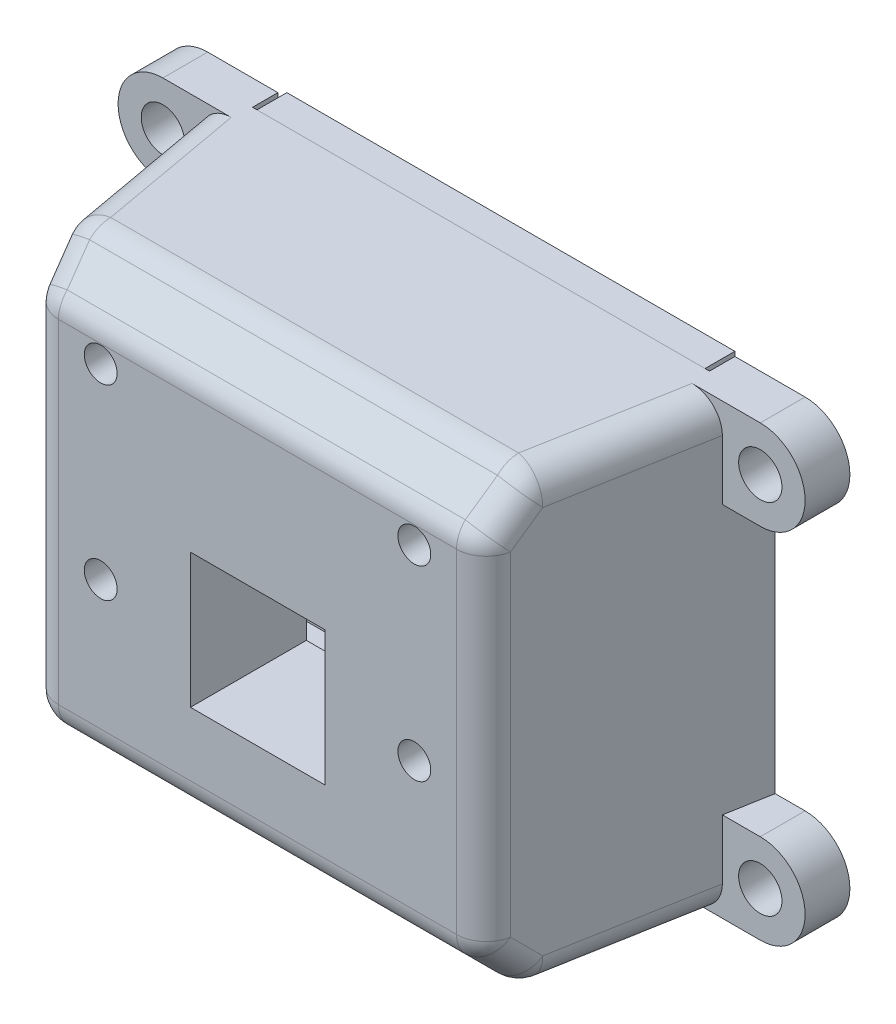
SolidWorks part; units mm, degrees
ref_plane "Front Plane" through (0, 0, 0) normal (0, 0, 1) x (1, 0, 0)
ref_plane "Top Plane" through (0, 0, 0) normal (0, 1, 0) x (1, 0, 0)
ref_plane "Right Plane" through (0, 0, 0) normal (1, 0, 0) x (0, 0, -1)
sketch "Sketch1" plane through (0, 0, 6.763) normal (0, 0, 1) x (1, 0, 0)
  line L1 (-15, -15) -> (15, -15)
  line L2 (-15, -15) -> (-15, 15)
  line L3 (-15, 15) -> (15, 15)
  line L4 (15, -15) -> (15, 15)
  line L5 (-15, -15) -> (15, 15) construction
  line L6 (-15, 15) -> (15, -15) construction
  point P0 (0, 0)
  dimension "D1" = 30
extrude "Boss-Extrude1" add sketch "Sketch1" along normal blind 2
sketch "Sketch2" plane through (0, 0, 6.763) normal (0, 0, -1) x (-1, 0, 0)
  line L0 (13, -15) -> (13, 13)
  line L1 (13, 13) -> (-13, 13)
  line L2 (-13, 13) -> (-13, -15)
  line L3 (-15, -15) -> (-13, -15)
  line L4 (-15, 15) -> (-15, -15)
  line L5 (-15, -15) -> (15, -15)
  line L6 (15, -15) -> (15, 15)
  line L7 (15, 15) -> (-15, 15)
  line L8 (-15, 15) -> (-15, -15)
  line L10 (15, -15) -> (15, 15)
  line L11 (15, 15) -> (-15, 15)
  line L12 (13, -15) -> (15, -15)
  dimension "D1" = 0
  dimension "D2" = 2
extrude "Boss-Extrude2" add sketch "Sketch2" along normal offset from surface (12.963 mm away) 3
sketch "Sketch3" plane through (0, 0, 6.763) normal (0, 0, -1) x (-1, 0, 0)
  line L0 (-10.5, 0.4953) -> (-13, 0.4953)
  line L1 (-13, 13) -> (-13, -15) construction
  line L2 (-13, 0.4953) -> (-13, -5.5047)
  line L3 (-13, -5.5047) -> (-10.5, -5.5047)
  line L4 (-13, 12.9953) -> (-10.5, 12.9953)
  line L5 (-13, -15) -> (-13, 13) construction
  line L6 (-10.5, 6.9953) -> (-13, 6.9953)
  line L7 (-13, 6.9953) -> (-13, 12.9953)
  line L8 (13, 12.9953) -> (10.5, 12.9953)
  line L9 (13, 13) -> (13, -15) construction
  line L10 (10.5, 6.9953) -> (13, 6.9953)
  line L12 (13, 6.9953) -> (13, 12.9953)
  line L13 (13, 0.4953) -> (10.5, 0.4953)
  line L14 (10.5, -5.5047) -> (13, -5.5047)
  line L15 (13, -5.5047) -> (13, 0.4953)
  circle A5 centre (-10.5, 9.9953) radius 1.1 construction
  arc A8 (-10.5, -5.5047) -> (-10.5, 0.4953) centre (-10.5, -2.5047) ccw
  arc A9 (-10.5, 12.9953) -> (-10.5, 6.9953) centre (-10.5, 9.9953) cw
  arc A11 (10.5, 12.9953) -> (10.5, 6.9953) centre (10.5, 9.9953) ccw
  arc A13 (10.5, 0.4953) -> (10.5, -5.5047) centre (10.5, -2.5047) ccw
  arc A15 (-12.5, -3.4212) -> (-12.5, -1.5882) centre (-10.5, -2.5047) ccw construction
  arc A16 (12.5, 9.9953) -> (10.5, 11.9953) centre (10.5, 9.9953) ccw construction
  arc A17 (12.5, -1.5882) -> (12.5, -3.4212) centre (10.5, -2.5047) ccw construction
  dimension "D1" = 6
extrude "Boss-Extrude3" add sketch "Sketch3" along normal up to surface (5.763 mm away)
sketch "Sketch4" plane through (0, 0, 6.763) normal (0, 0, -1) x (-1, 0, 0)
  line L1 (13, -12.3667) -> (-13, -12.3667)
  line L2 (13, -12.3667) -> (13, -15)
  line L3 (13, -15) -> (-13, -15)
  line L4 (-13, -12.3667) -> (-13, -15)
  line L5 (-11.0493, -11.8667) -> (11.1507, -11.8667) construction
  line L6 (-11.0493, -11.8667) -> (11.1507, -11.8667) construction
  line L7 (13, 6.9953) -> (13, 0.4953) construction
  dimension "D1" = 0.5
extrude "Boss-Extrude4" add sketch "Sketch4" along normal up to surface (6.763 mm away) up to plane "Front Plane"
sketch "Sketch6" plane through (0, 0, -6.2) normal (0, 0, -1) x (-1, 0, 0)
  line L1 (-15, 15) -> (15, 15)
  line L2 (-15, 15) -> (-15, -15)
  line L3 (-15, -15) -> (15, -15)
  line L4 (15, 15) -> (15, -15)
extrude "Boss-Extrude5" add sketch "Sketch6" along normal blind 2 separate body
sketch "Sketch8" plane through (0, 0, 8.763) normal (0, 0, 1) x (1, 0, 0)
  line L0 (-3.9917, 1.5922) -> (-3.9917, -6.4078) construction
  line L1 (-3.9917, -6.4078) -> (4.0083, -6.4078) construction
  line L2 (4.0083, -6.4078) -> (4.0083, 1.5922) construction
  line L3 (4.0083, 1.5922) -> (-3.9917, 1.5922) construction
  line L4 (-3.9917, 1.5922) -> (-3.9917, -6.4078) construction
  line L5 (-3.9917, -6.4078) -> (4.0083, -6.4078) construction
  line L6 (4.0083, -6.4078) -> (4.0083, 1.5922) construction
  line L7 (4.0083, 1.5922) -> (-3.9917, 1.5922) construction
  line L8 (-4.4917, 2.0922) -> (-4.4917, -6.9078)
  line L9 (-4.4917, -6.9078) -> (4.5083, -6.9078)
  line L10 (4.5083, -6.9078) -> (4.5083, 2.0922)
  line L11 (4.5083, 2.0922) -> (-4.4917, 2.0922)
  dimension "D1" = 0.5
extrude "Cut-Extrude1" cut sketch "Sketch8" against normal through all
sketch "Sketch9" plane through (0, 0, 6.763) normal (0, 0, -1) x (-1, 0, 0)
  line L0 (5.4917, -7.9078) -> (5.4917, 3.0922)
  line L1 (5.4917, 3.0922) -> (-5.5083, 3.0922)
  line L2 (-5.5083, 3.0922) -> (-5.5083, -7.9078)
  line L3 (-5.5083, -7.9078) -> (5.4917, -7.9078)
  line L4 (4.4917, -6.9078) -> (4.4917, 2.0922)
  line L5 (-4.5083, -6.9078) -> (4.4917, -6.9078)
  line L6 (-4.5083, 2.0922) -> (-4.5083, -6.9078)
  line L7 (4.4917, 2.0922) -> (-4.5083, 2.0922)
  line L8 (4.4917, -6.9078) -> (4.4917, 2.0922)
  line L9 (-4.5083, -6.9078) -> (4.4917, -6.9078)
  line L10 (-4.5083, 2.0922) -> (-4.5083, -6.9078)
  line L11 (4.4917, 2.0922) -> (-4.5083, 2.0922)
  dimension "D1" = 0
  dimension "D2" = 1
extrude "Boss-Extrude7" add sketch "Sketch9" along normal up to surface (5.763 mm away)
sketch "Sketch10" plane through (0, 0, 1) normal (0, 0, -1) x (-1, 0, 0)
  line L0 (5.4917, 3.0922) -> (-5.5083, 3.0922) construction
  line L1 (4.4917, 2.0922) -> (-4.5083, 2.0922)
  line L2 (4.4917, 2.0922) -> (4.4917, 3.0922)
  line L3 (4.4917, 3.0922) -> (-4.5083, 3.0922)
  line L4 (-4.5083, 2.0922) -> (-4.5083, 3.0922)
extrude "Cut-Extrude2" cut sketch "Sketch10" against normal offset from surface (2.1 mm away) 1
sketch "Sketch11" plane through (0, 0, 6.763) normal (0, 0, -1) x (-1, 0, 0)
  line L0 (13, -15) -> (13, 13) construction
  line L1 (-13, 13) -> (13, 13)
  line L2 (-13, 13) -> (-13, 12.999)
  line L3 (-13, 12.999) -> (13, 12.999)
  line L4 (13, 13) -> (13, 12.999)
  dimension "D1" = 0.001
extrude "Boss-Extrude8" add sketch "Sketch11" along normal up to surface (12.963 mm away)
sketch "Sketch13" plane through (0, -15, 0) normal (0, -1, 0) x (1, 0, 0)
  line L0 (13, -6.2) -> (15, -6.2) construction
  line L1 (13.75, -6.2) -> (13, -6.2)
  line L2 (13.75, -6.2) -> (13.75, 0)
  line L3 (13.75, 0) -> (13, 0)
  line L4 (13, -6.2) -> (13, 0)
  line L5 (13, -6.2) -> (13, 0) construction
  line L6 (-13, 0) -> (13, 0) construction
  line L7 (15, 8.763) -> (15, -6.2) construction
  line L8 (0, 5.5223) -> (0, 0) construction
  line L14 (-13, -6.2) -> (-13, 0)
  line L15 (-13.75, 0) -> (-13, 0)
  line L16 (-13.75, -6.2) -> (-13.75, 0)
  line L17 (-13.75, -6.2) -> (-13, -6.2)
  dimension "D1" = 1.25
extrude "Cut-Extrude3" cut sketch "Sketch13" against normal up to surface (27.999 mm away) up to face at (0, 12.999, 0.2815)
sketch "Sketch7" plane through (0, -15, 0) normal (0, -1, 0) x (1, 0, 0)
  line L0 (15, -6.2) -> (-15, -6.2) construction
  line L1 (13.5, -6.2) -> (-13.5, -6.2)
  line L2 (13.5, -6.2) -> (13.5, -0.25)
  line L3 (13.5, -0.25) -> (-13.5, -0.25)
  line L4 (-13.5, -6.2) -> (-13.5, -0.25)
  line L5 (13.75, -0.25) -> (13.5, -0.25) construction
  line L7 (13.5, 0) -> (13.5, -0.25) construction
  line L8 (-13.75, 0) -> (13.75, 0) construction
  line L9 (-13.75, -0.25) -> (-13.5, -0.25) construction
  line L10 (-13.75, 0) -> (-13.75, -6.2) construction
  line L11 (13.75, -6.2) -> (13.75, 0) construction
  dimension "D1" = 0.25
extrude "Boss-Extrude6" add sketch "Sketch7" against normal blind 2
sketch "Sketch12" plane through (0, -15, 0) normal (0, -1, 0) x (1, 0, 0)
  line L0 (13.5, -0.25) -> (-13.5, -0.25) construction
  line L1 (-12.5, -0.25) -> (-13.5, -0.25)
  line L2 (-12.5, -0.25) -> (-12.5, -6.2)
  line L3 (-12.5, -6.2) -> (-13.5, -6.2)
  line L4 (-13.5, -0.25) -> (-13.5, -6.2)
  line L6 (12.5, -0.25) -> (13.5, -0.25)
  line L7 (12.5, -0.25) -> (12.5, -6.2)
  line L8 (12.5, -6.2) -> (13.5, -6.2)
  line L9 (13.5, -0.25) -> (13.5, -6.2)
  dimension "D1" = 1
extrude "Boss-Extrude10" add sketch "Sketch12" against normal up to surface (27.999 mm away) up to face at (0, 12.999, 0.1407)
sketch "Sketch17" plane through (0, -15, 0) normal (0, -1, 0) x (1, 0, 0)
  line L0 (15, 8.763) -> (18, -7.9)
  line L1 (18, -7.9) -> (15.3, -7.9)
  line L2 (15.3, -7.9) -> (15.3, -6.2)
  line L3 (15.3, -6.2) -> (15, -6.2)
  line L4 (15, -6.2) -> (15, 8.763)
  line L5 (15, -8.2) -> (15, -6.2) construction
  line L7 (15, 8.763) -> (15, -6.2) construction
  line L8 (0, 0) -> (0, 4.7808) construction
  line L10 (-15.3, -6.2) -> (-15, -6.2)
  line L11 (-15.3, -7.9) -> (-15.3, -6.2)
  line L12 (-18, -7.9) -> (-15.3, -7.9)
  line L13 (-15, 8.763) -> (-18, -7.9)
  line L14 (-15, -6.2) -> (-15, 8.763)
  line L15 (15, -8.2) -> (-15, -8.2) construction
  dimension "D1" = 0.3
  dimension "D2" = 3
  dimension "D3" = 0.3
extrude "Boss-Extrude12" add sketch "Sketch17" against normal up to surface (30 mm away) up to face at (0, 15, 1.2815)
sketch "Sketch18" plane through (0, 0, -7.9) normal (0, 0, -1) x (-1, 0, 0)
  line L1 (-20, -12) -> (20, -12)
  line L2 (-20, -12) -> (-20, 12)
  line L3 (-20, 12) -> (20, 12)
  line L4 (20, -12) -> (20, 12)
  line L5 (-20, -12) -> (20, 12) construction
  line L6 (-20, 12) -> (20, -12) construction
  point P0 (0, 0)
  dimension "D1" = 40
  dimension "D2" = 24
sketch "Sketch19" plane through (0, 0, -7.9) normal (0, 0, -1) x (-1, 0, 0)
  line L0 (-15.3, 15) -> (-20, 15)
  line L1 (-20, -12) -> (-20, 12) construction
  line L2 (-20, 9) -> (-15.3, 9)
  line L4 (-15.3, 9) -> (-15.3, 15)
  line L5 (15.3, 15) -> (20, 15)
  line L6 (20, 9) -> (15.3, 9)
  line L8 (15.3, 9) -> (15.3, 15)
  line L9 (-15.3, -15) -> (-20, -15)
  line L10 (-20, -9) -> (-15.3, -9)
  line L11 (-15.3, -9) -> (-15.3, -15)
  line L12 (15.3, -15) -> (20, -15)
  line L13 (20, -12) -> (20, 12) construction
  line L14 (20, -9) -> (15.3, -9)
  line L15 (15.3, -9) -> (15.3, -15)
  line L16 (-15.3, 15) -> (-15.3, -15) construction
  arc A0 (-20, 15) -> (-20, 9) centre (-20, 12) ccw
  arc A1 (20, 15) -> (20, 9) centre (20, 12) cw
  arc A2 (-20, -15) -> (-20, -9) centre (-20, -12) cw
  arc A3 (20, -15) -> (20, -9) centre (20, -12) ccw
extrude "Boss-Extrude13" add sketch "Sketch19" against normal blind 3
hole_wizard "M2.5 Clearance Hole1" positions "Sketch20" profile "Sketch21" hole size "M2.5" standard "ANSI Metric" end condition through all
sketch "Sketch20" plane through (0, 0, -4.9) normal (0, 0, 1) x (1, 0, 0)
  point P0 (-20, 12)
  point P3 (20, 12)
  point P6 (20, -12)
  point P9 (-20, -12)
sketch "Sketch21" plane through (-20, 12, -4.9) normal (1, 0, 0) x (0, -1, 0)
  line L0 (0, 0) -> (0, 3.3)
  line L1 (0, 3.3) -> (1.45, 3.3)
  line L2 (1.45, 3.3) -> (1.45, 0)
  line L5 (1.45, 0) -> (0, 0)
  line L11 (0, -6.35) -> (0, 107.95) construction
  dimension "Thru Hole Dia." = 2.9
  dimension "Thru Hole Depth" = 3.3
chamfer "Chamfer1" distance 3 angle 45 2 edges at (0, 15, 8.763) (0, -15, 8.763)
sketch "Sketch22" plane through (0, -15, 0) normal (0, -1, 0) x (1, 0, 0)
  line L0 (13.5, -0.25) -> (-13.5, -0.25) construction
  line L1 (-9.1507, -0.25) -> (9.1507, -0.25)
  line L2 (-9.1507, -0.25) -> (-9.1507, -1.9)
  line L3 (-9.1507, -1.9) -> (9.1507, -1.9)
  line L4 (9.1507, -0.25) -> (9.1507, -1.9)
  line L5 (8.2493, -1.4) -> (-8.1507, -1.4) construction
  line L6 (8.2493, -1.4) -> (-8.1507, -1.4) construction
  line L7 (-8.1507, 0) -> (-8.1507, -1.4) construction
  line L8 (-8.1507, 0) -> (-8.1507, -1.4) construction
  point P4 (0, -0.25)
  dimension "D1" = 0.5
  dimension "D2" = 1
extrude "Cut-Extrude5" cut sketch "Sketch22" against normal up to surface (2 mm away) up to face at (0, -13, -3.225)
hole_wizard "M2 Clearance Hole1" positions "Sketch24" profile "Sketch25" hole size "M2" standard "ANSI Metric" end condition through all
sketch "Sketch24" plane through (0, 0, 1) normal (0, 0, -1) x (-1, 0, 0)
  point P0 (-10.5, 9.9953)
  point P3 (10.5, 9.9953)
  point P6 (10.5, -2.5047)
  point P9 (-10.5, -2.5047)
sketch "Sketch25" plane through (10.5, 9.9953, 1) normal (1, 0, 0) x (0, 1, 0)
  line L0 (0, 0) -> (0, 7.763)
  line L1 (0, 7.763) -> (1.1, 7.763)
  line L2 (1.1, 7.763) -> (1.1, 0)
  line L5 (1.1, 0) -> (0, 0)
  line L11 (0, -6.35) -> (0, 107.95) construction
  dimension "Thru Hole Dia." = 2.2
  dimension "Thru Hole Depth" = 7.763
chamfer "Chamfer2" distance 0.5 angle 45 4 edges at (-11.6, -2.5047, 1) (-11.6, 9.9953, 1) (9.4, -2.5047, 1) (9.4, 9.9953, 1)
fillet "Fillet1" radius 2 14 edges at (-16.5, -15, 0.4315) (16.5, -15, 0.4315) (-15.2701, -13.5, 7.263) (0, -15, 5.763) (15.2701, -13.5, 7.263) (0, -12, 8.763) (15, 0, 8.763) (-16.5, 15, 0.4315) (16.5, 15, 0.4315) (15.2701, 13.5, 7.263) (-15.2701, 13.5, 7.263) (0, 15, 5.763) (0, 12, 8.763) (-15, 0, 8.763)
